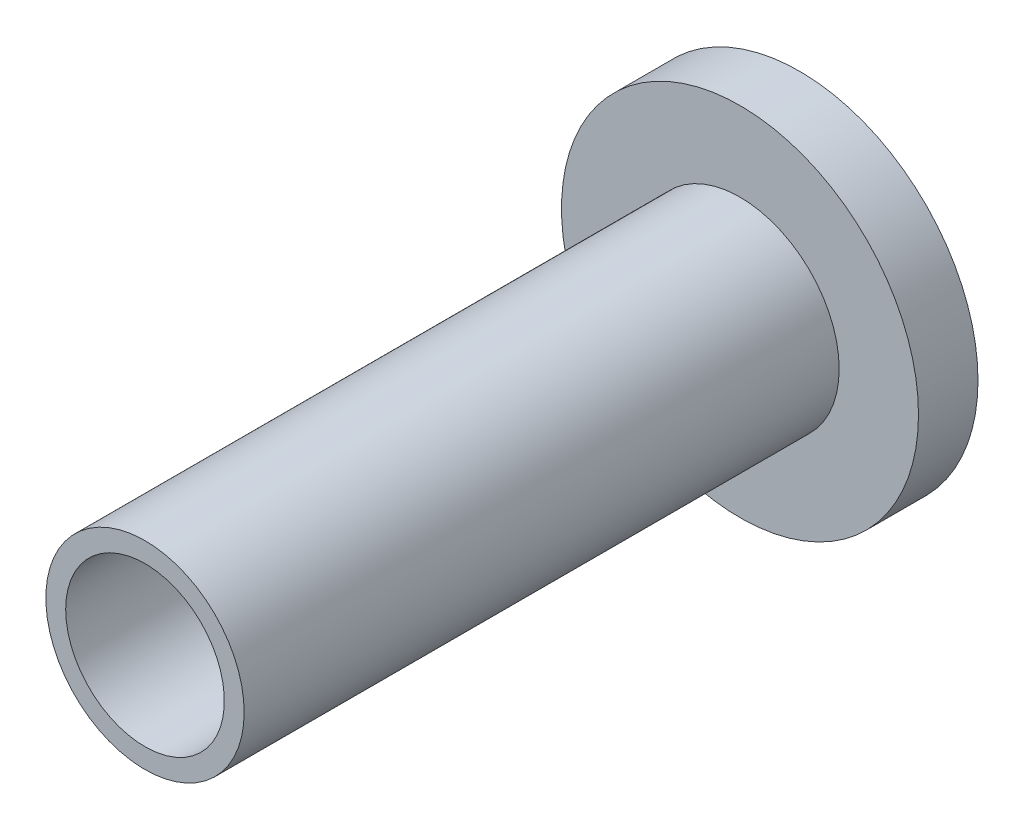
SolidWorks part; units mm, degrees
ref_plane "Plan de face" through (0, 0, 0) normal (0, 0, 1) x (1, 0, 0)
ref_plane "Plan de dessus" through (0, 0, 0) normal (0, 1, 0) x (1, 0, 0)
ref_plane "Plan de droite" through (0, 0, 0) normal (1, 0, 0) x (0, 0, -1)
sketch "Esquisse1" plane through (0, 0, 0) normal (0, 0, 1) x (1, 0, 0)
  circle A0 centre (0, 0) radius 2.5
  dimension "D1" = 5
extrude "Boss.-Extru.1" add sketch "Esquisse1" along normal blind 15
sketch "Esquisse2" plane through (0, 0, 0) normal (0, 0, 1) x (1, 0, 0)
  line L1 (-1.7187, 0.1158) -> (1.7187, 0.1158)
  line L2 (-1.7187, 0.1158) -> (-1.7187, -0.1158)
  line L3 (-1.7187, -0.1158) -> (1.7187, -0.1158)
  line L4 (1.7187, 0.1158) -> (1.7187, -0.1158)
  line L5 (-1.7187, 0.1158) -> (1.7187, -0.1158) construction
  line L6 (-1.7187, -0.1158) -> (1.7187, 0.1158) construction
  line L7 (-0.1158, -1.7187) -> (0.1158, -1.7187)
  line L8 (-0.1158, -1.7187) -> (-0.1158, 1.7187)
  line L9 (-0.1158, 1.7187) -> (0.1158, 1.7187)
  line L10 (0.1158, -1.7187) -> (0.1158, 1.7187)
  line L11 (-0.1158, -1.7187) -> (0.1158, 1.7187) construction
  line L12 (-0.1158, 1.7187) -> (0.1158, -1.7187) construction
  circle A0 centre (0, 0) radius 4.5
  dimension "D1" = 9
extrude "Boss.-Extru.2" add sketch "Esquisse2" against normal blind 1.5 contours A0 L10 L7 L8 L3 L2 L1 L9 L4
sketch "Esquisse3" plane through (0, 0, 15) normal (0, 0, 1) x (1, 0, 0)
  circle A0 centre (0, 0) radius 2
  dimension "D1" = 4
extrude "Enlèv. mat.-Extru.1" cut sketch "Esquisse3" against normal blind 10 and the other way through all
cosmetic thread "Représentation de filetage1" parameters "D2"=5
